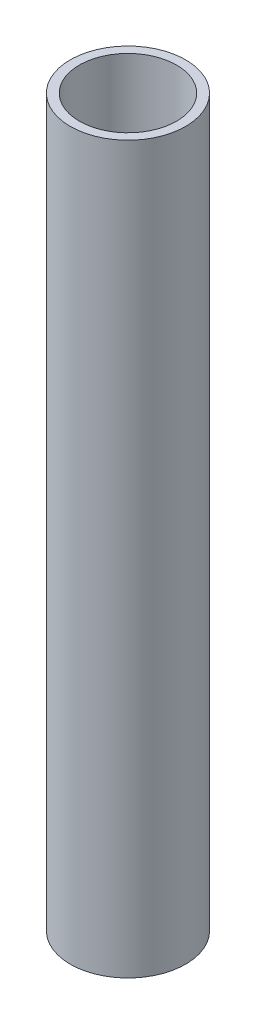
SolidWorks part; units mm, degrees
ref_plane "Front Plane" through (0, 0, 0) normal (0, 0, 1) x (1, 0, 0)
ref_plane "Top Plane" through (0, 0, 0) normal (0, 1, 0) x (1, 0, 0)
ref_plane "Right Plane" through (0, 0, 0) normal (1, 0, 0) x (0, 0, -1)
sketch "Sketch1" plane through (0, 0, 0) normal (0, 1, 0) x (1, 0, 0)
  circle A0 centre (0, 0) radius 15.905
  circle A1 centre (0, 0) radius 13.405
  dimension "D1" = 31.81
  dimension "D2" = 2.5
extrude "Boss-Extrude1" add sketch "Sketch1" against normal blind 200
